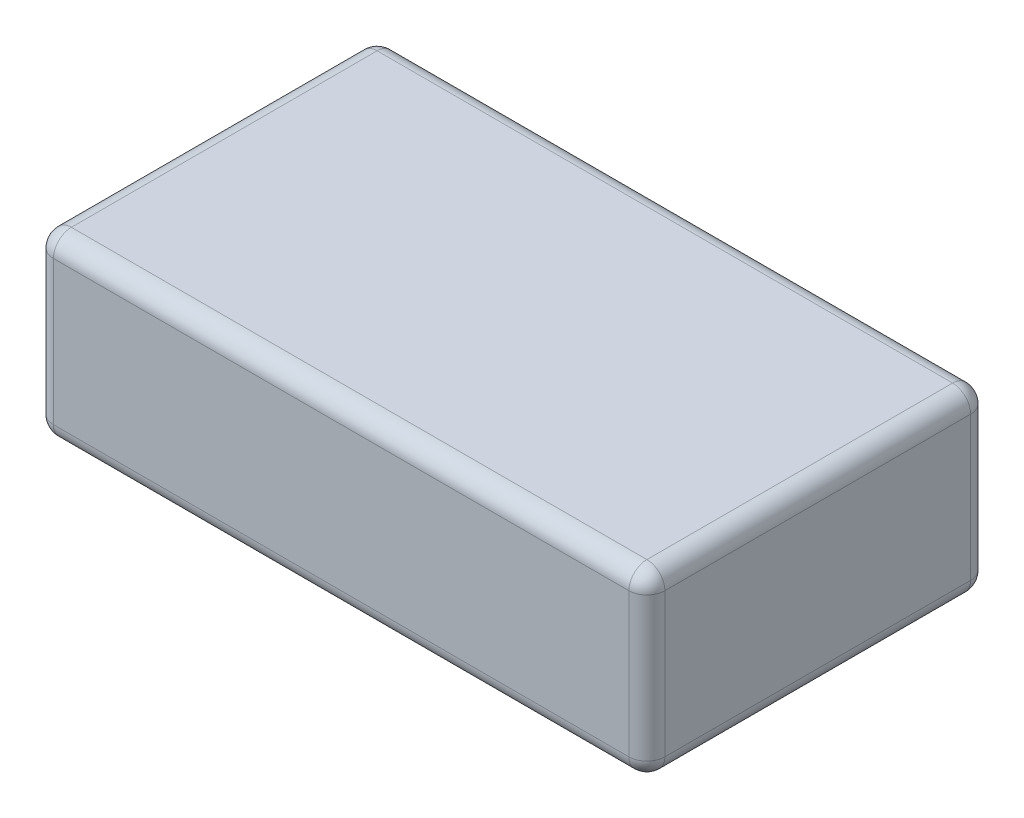
SolidWorks part; units mm, degrees
ref_plane "Front Plane" through (0, 0, 0) normal (0, 0, 1) x (1, 0, 0)
ref_plane "Top Plane" through (0, 0, 0) normal (0, 1, 0) x (1, 0, 0)
ref_plane "Right Plane" through (0, 0, 0) normal (1, 0, 0) x (0, 0, -1)
sketch "Sketch1" plane through (0, 0, 0) normal (0, 1, 0) x (1, 0, 0)
  line L1 (-34, 19) -> (34, 19)
  line L2 (-34, 19) -> (-34, -19)
  line L3 (-34, -19) -> (34, -19)
  line L4 (34, 19) -> (34, -19)
  line L5 (-34, 19) -> (34, -19) construction
  line L6 (-34, -19) -> (34, 19) construction
  point P0 (0, 0)
  dimension "D1" = 68
  dimension "D2" = 38
extrude "Boss-Extrude1" add sketch "Sketch1" along normal blind 20
fillet "Fillet1" radius 2 12 edges at (-34, 10, 19) (34, 10, 19) (0, 0, 19) (34, 10, -19) (-34, 10, -19) (0, 0, -19) (0, 20, 19) (-34, 20, 0) (0, 20, -19) (34, 20, 0) (-34, 0, 0) (34, 0, 0)
